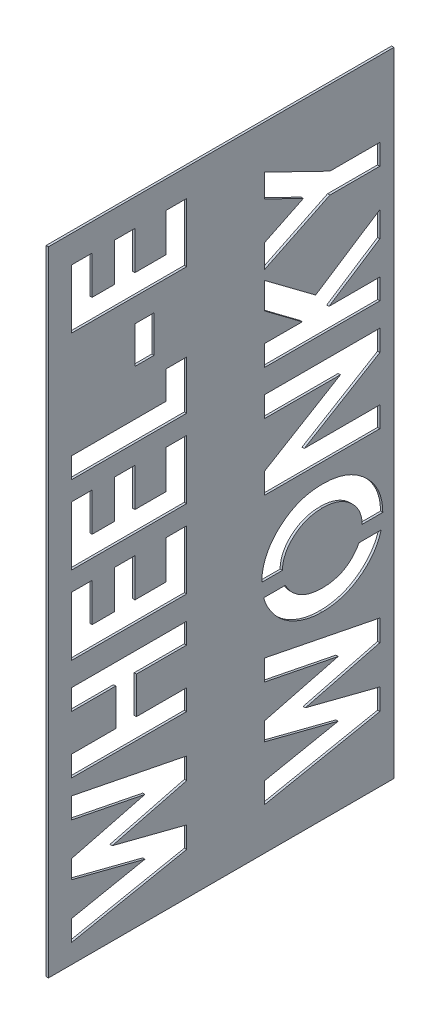
SolidWorks part; units mm, degrees
ref_plane "Front Plane" through (0, 0, 0) normal (1, 0, 0) x (0, 1, 0)
ref_plane "Top Plane" through (0, 0, 0) normal (0, 0, 1) x (0, 1, 0)
ref_plane "Right Plane" through (0, 0, 0) normal (0, 1, 0) x (-1, 0, 0)
sketch "Sketch2" plane through (0, 0, 0) normal (1, 0, 0) x (0, 1, 0)
  line L1 (-55, 24) -> (55, 24)
  line L2 (-55, 24) -> (-55, -36)
  line L3 (-55, -36) -> (55, -36)
  line L4 (55, 24) -> (55, -36)
  point P5 (0, -36)
  dimension "D1" = 110
  dimension "D2" = 60
  dimension "D3" = 24
extrude "Boss-Extrude1" add sketch "Sketch2" along normal blind 0.4
sketch "Sketch1" plane through (0, 0, 0) normal (1, 0, 0) x (0, 1, 0)
  line L0 (0.0005, 0) -> (0.0429, 0) construction
  line L1 (-55, 0) -> (55, 0) construction
  text T0 "<b>WHEEL-E</b>\r\n<b>WONKY</b>" font "Century Gothic" height 20
  dimension "D1" = 110
  dimension "D2" = 55
extrude "Cut-Extrude1" cut sketch "Sketch1" along normal blind 1.5
sketch "Sketch3" plane through (0.4, 0, 0) normal (1, 0, 0) x (0, 1, 0)
  line L1 (-16.5, -13) -> (-14, -13)
  line L2 (-16.5, -13) -> (-16.5, -35)
  line L3 (-16.5, -35) -> (-14, -35)
  line L4 (-14, -13) -> (-14, -35)
  dimension "D1" = 22
  dimension "D2" = 14
  dimension "24.5" = 35
  dimension "D3" = 2.5
extrude "Boss-Extrude2" add sketch "Sketch3" against normal up to surface (0.4 mm away) up to face at (0, -14.0775, -23.5771)
